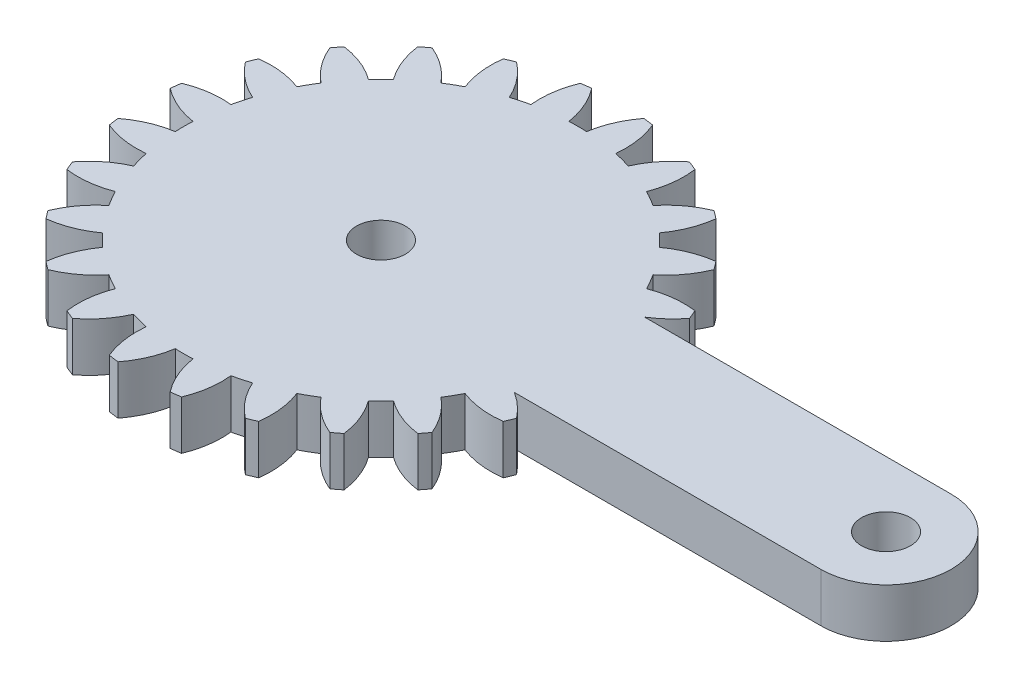
SolidWorks part; units mm, degrees
ref_plane "Front" through (0, 0, 0) normal (0, 0, 1) x (1, 0, 0)
ref_plane "Top" through (0, 0, 0) normal (0, 1, 0) x (1, 0, 0)
ref_plane "Right" through (0, 0, 0) normal (1, 0, 0) x (0, 0, -1)
sketch "Sketch1" plane through (0, 0, 0) normal (0, 1, 0) x (1, 0, 0)
  line L0 (11.068, -3.7704) -> (29.88, -3.7704)
  line L1 (29.88, 4.2296) -> (11.068, 4.2296)
  circle A0 centre (29.88, 0.2296) radius 1.5
  arc A1 (12.5081, -5.0775) -> (11.068, -3.7704) centre (8.218, -8.3571) ccw
  arc A2 (12.2692, -5.6542) -> (12.5081, -5.0775) centre (-1.12, 0.2296) ccw
  arc A3 (9.6134, -5.3407) -> (12.2692, -5.6542) centre (11.5547, -0.3017) ccw
  arc A4 (9.0707, -6.2807) -> (9.6134, -5.3407) centre (-1.12, 0.2296) ccw
  arc A5 (10.6701, -8.4239) -> (9.0707, -6.2807) centre (5.6774, -10.4814) ccw
  arc A6 (10.2901, -8.9191) -> (10.6701, -8.4239) centre (-1.12, 0.2296) ccw
  arc A7 (7.806, -7.9289) -> (10.2901, -8.9191) centre (10.9853, -3.564) ccw
  arc A8 (7.0385, -8.6964) -> (7.806, -7.9289) centre (-1.12, 0.2296) ccw
  arc A9 (8.0287, -11.1806) -> (7.0385, -8.6964) centre (2.6736, -11.8757) ccw
  arc A10 (7.5335, -11.5605) -> (8.0287, -11.1806) centre (-1.12, 0.2296) ccw
  arc A11 (5.3903, -9.9611) -> (7.5335, -11.5605) centre (9.591, -6.5678) ccw
  arc A12 (4.4502, -10.5038) -> (5.3903, -9.9611) centre (-1.12, 0.2296) ccw
  arc A13 (4.7638, -13.1596) -> (4.4502, -10.5038) centre (-0.5887, -12.4451) ccw
  arc A14 (4.1871, -13.3985) -> (4.7638, -13.1596) centre (-1.12, 0.2296) ccw
  arc A15 (2.5309, -11.2988) -> (4.1871, -13.3985) centre (7.4667, -9.1084) ccw
  arc A16 (1.4824, -11.5798) -> (2.5309, -11.2988) centre (-1.12, 0.2296) ccw
  arc A17 (1.0979, -14.2262) -> (1.4824, -11.5798) centre (-3.8873, -12.1507) ccw
  arc A18 (0.4791, -14.3077) -> (1.0979, -14.2262) centre (-1.12, 0.2296) ccw
  arc A19 (-0.5773, -11.851) -> (0.4791, -14.3077) centre (4.7572, -11.0127) ccw
  arc A20 (-1.6627, -11.851) -> (-0.5773, -11.851) centre (-1.12, 0.2296) ccw
  arc A21 (-2.7191, -14.3077) -> (-1.6627, -11.851) centre (-6.9973, -11.0127) ccw
  arc A22 (-3.338, -14.2262) -> (-2.7191, -14.3077) centre (-1.12, 0.2296) ccw
  arc A23 (-3.7225, -11.5798) -> (-3.338, -14.2262) centre (1.6473, -12.1507) ccw
  arc A24 (-4.7709, -11.2988) -> (-3.7225, -11.5798) centre (-1.12, 0.2296) ccw
  arc A25 (-6.4272, -13.3985) -> (-4.7709, -11.2988) centre (-9.7067, -9.1084) ccw
  arc A26 (-7.0038, -13.1596) -> (-6.4272, -13.3985) centre (-1.12, 0.2296) ccw
  arc A27 (-6.6903, -10.5038) -> (-7.0038, -13.1596) centre (-1.6513, -12.4451) ccw
  arc A28 (-7.6303, -9.9611) -> (-6.6903, -10.5038) centre (-1.12, 0.2296) ccw
  arc A29 (-9.7735, -11.5605) -> (-7.6303, -9.9611) centre (-11.831, -6.5678) ccw
  arc A30 (-10.2687, -11.1806) -> (-9.7735, -11.5605) centre (-1.12, 0.2296) ccw
  arc A31 (-9.2785, -8.6964) -> (-10.2687, -11.1806) centre (-4.9137, -11.8757) ccw
  arc A32 (-10.046, -7.9289) -> (-9.2785, -8.6964) centre (-1.12, 0.2296) ccw
  arc A33 (-12.5302, -8.9191) -> (-10.046, -7.9289) centre (-13.2254, -3.564) ccw
  arc A34 (-12.9102, -8.4239) -> (-12.5302, -8.9191) centre (-1.12, 0.2296) ccw
  arc A35 (-11.3107, -6.2807) -> (-12.9102, -8.4239) centre (-7.9175, -10.4814) ccw
  arc A36 (-11.8535, -5.3407) -> (-11.3107, -6.2807) centre (-1.12, 0.2296) ccw
  arc A37 (-14.5093, -5.6542) -> (-11.8535, -5.3407) centre (-13.7947, -0.3017) ccw
  arc A38 (-14.7481, -5.0775) -> (-14.5093, -5.6542) centre (-1.12, 0.2296) ccw
  arc A39 (-12.6485, -3.4213) -> (-14.7481, -5.0775) centre (-10.4581, -8.3571) ccw
  arc A40 (-12.9294, -2.3728) -> (-12.6485, -3.4213) centre (-1.12, 0.2296) ccw
  arc A41 (-15.5759, -1.9883) -> (-12.9294, -2.3728) centre (-13.5004, 2.9969) ccw
  arc A42 (-15.6573, -1.3695) -> (-15.5759, -1.9883) centre (-1.12, 0.2296) ccw
  arc A43 (-13.2006, -0.3131) -> (-15.6573, -1.3695) centre (-12.3623, -5.6476) ccw
  arc A44 (-13.2006, 0.7723) -> (-13.2006, -0.3131) centre (-1.12, 0.2296) ccw
  arc A45 (-15.6573, 1.8287) -> (-13.2006, 0.7723) centre (-12.3623, 6.1069) ccw
  arc A46 (-15.5759, 2.4475) -> (-15.6573, 1.8287) centre (-1.12, 0.2296) ccw
  arc A47 (-12.9294, 2.8321) -> (-15.5759, 2.4475) centre (-13.5004, -2.5377) ccw
  arc A48 (-12.6485, 3.8805) -> (-12.9294, 2.8321) centre (-1.12, 0.2296) ccw
  arc A49 (-14.7481, 5.5368) -> (-12.6485, 3.8805) centre (-10.4581, 8.8163) ccw
  arc A50 (-14.5093, 6.1134) -> (-14.7481, 5.5368) centre (-1.12, 0.2296) ccw
  arc A51 (-11.8535, 5.7999) -> (-14.5093, 6.1134) centre (-13.7947, 0.7609) ccw
  arc A52 (-11.3107, 6.7399) -> (-11.8535, 5.7999) centre (-1.12, 0.2296) ccw
  arc A53 (-12.9102, 8.8831) -> (-11.3107, 6.7399) centre (-7.9175, 10.9406) ccw
  arc A54 (-12.5302, 9.3783) -> (-12.9102, 8.8831) centre (-1.12, 0.2296) ccw
  arc A55 (-10.046, 8.3881) -> (-12.5302, 9.3783) centre (-13.2254, 4.0233) ccw
  arc A56 (-9.2785, 9.1556) -> (-10.046, 8.3881) centre (-1.12, 0.2296) ccw
  arc A57 (-10.2687, 11.6398) -> (-9.2785, 9.1556) centre (-4.9137, 12.3349) ccw
  arc A58 (-9.7735, 12.0198) -> (-10.2687, 11.6398) centre (-1.12, 0.2296) ccw
  arc A59 (-7.6303, 10.4203) -> (-9.7735, 12.0198) centre (-11.831, 7.0271) ccw
  arc A60 (-6.6903, 10.9631) -> (-7.6303, 10.4203) centre (-1.12, 0.2296) ccw
  arc A61 (-7.0038, 13.6188) -> (-6.6903, 10.9631) centre (-1.6513, 12.9043) ccw
  arc A62 (-6.4272, 13.8577) -> (-7.0038, 13.6188) centre (-1.12, 0.2296) ccw
  arc A63 (-4.7709, 11.7581) -> (-6.4272, 13.8577) centre (-9.7067, 9.5677) ccw
  arc A64 (-3.7225, 12.039) -> (-4.7709, 11.7581) centre (-1.12, 0.2296) ccw
  arc A65 (-3.338, 14.6855) -> (-3.7225, 12.039) centre (1.6473, 12.61) ccw
  arc A66 (-2.7191, 14.7669) -> (-3.338, 14.6855) centre (-1.12, 0.2296) ccw
  arc A67 (-1.6627, 12.3102) -> (-2.7191, 14.7669) centre (-6.9973, 11.4719) ccw
  arc A68 (-0.5773, 12.3102) -> (-1.6627, 12.3102) centre (-1.12, 0.2296) ccw
  arc A69 (0.4791, 14.7669) -> (-0.5773, 12.3102) centre (4.7572, 11.4719) ccw
  arc A70 (1.0979, 14.6855) -> (0.4791, 14.7669) centre (-1.12, 0.2296) ccw
  arc A71 (1.4824, 12.039) -> (1.0979, 14.6855) centre (-3.8873, 12.61) ccw
  arc A72 (2.5309, 11.7581) -> (1.4824, 12.039) centre (-1.12, 0.2296) ccw
  arc A73 (4.1871, 13.8577) -> (2.5309, 11.7581) centre (7.4667, 9.5677) ccw
  arc A74 (4.7638, 13.6188) -> (4.1871, 13.8577) centre (-1.12, 0.2296) ccw
  arc A75 (4.4502, 10.9631) -> (4.7638, 13.6188) centre (-0.5887, 12.9043) ccw
  arc A76 (5.3903, 10.4203) -> (4.4502, 10.9631) centre (-1.12, 0.2296) ccw
  arc A77 (7.5335, 12.0198) -> (5.3903, 10.4203) centre (9.591, 7.0271) ccw
  arc A78 (8.0287, 11.6398) -> (7.5335, 12.0198) centre (-1.12, 0.2296) ccw
  arc A79 (7.0385, 9.1556) -> (8.0287, 11.6398) centre (2.6736, 12.3349) ccw
  arc A80 (7.806, 8.3881) -> (7.0385, 9.1556) centre (-1.12, 0.2296) ccw
  arc A81 (10.2901, 9.3783) -> (7.806, 8.3881) centre (10.9853, 4.0233) ccw
  arc A82 (10.6701, 8.8831) -> (10.2901, 9.3783) centre (-1.12, 0.2296) ccw
  arc A83 (9.0707, 6.7399) -> (10.6701, 8.8831) centre (5.6774, 10.9406) ccw
  arc A84 (9.6134, 5.7999) -> (9.0707, 6.7399) centre (-1.12, 0.2296) ccw
  arc A85 (12.2692, 6.1134) -> (9.6134, 5.7999) centre (11.5547, 0.7609) ccw
  arc A86 (12.5081, 5.5368) -> (12.2692, 6.1134) centre (-1.12, 0.2296) ccw
  arc A87 (11.068, 4.2296) -> (12.5081, 5.5368) centre (8.218, 8.8163) ccw
  arc A88 (29.88, -3.7704) -> (29.88, 4.2296) centre (29.88, 0.2296) ccw
  circle A89 centre (-1.12, 0.2296) radius 1.5
  dimension "D1" = 3
  dimension "D2" = 12.0927
extrude "Boss-Extrude1" add sketch "Sketch1" along normal mid plane 3
